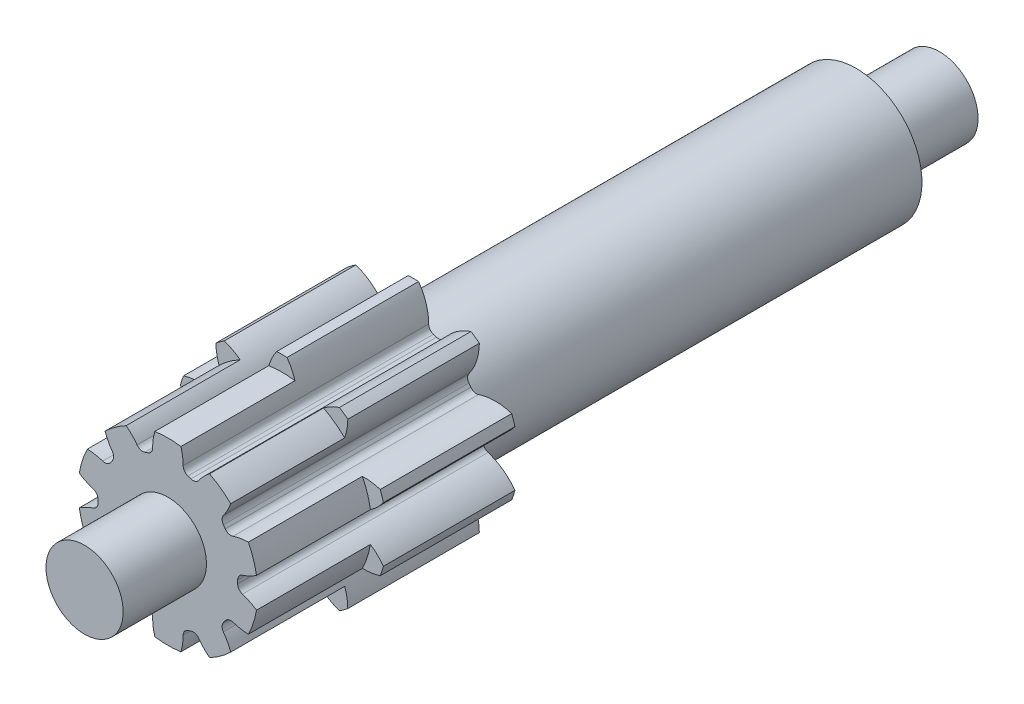
SolidWorks part; units mm, degrees
ref_plane "Front Plane" through (0, 0, 0) normal (0, 0, 1) x (1, 0, 0)
ref_plane "Top Plane" through (0, 0, 0) normal (0, 1, 0) x (1, 0, 0)
ref_plane "Right Plane" through (0, 0, 0) normal (1, 0, 0) x (0, 0, -1)
sketch "Sketch1" plane through (0, 0, 0) normal (0, 0, 1) x (1, 0, 0)
  line L0 (0, 0) -> (0, 1) construction
  line L1 (-0.3214, 1.117) -> (0.3214, 0.883) construction
  circle A0 centre (0, 0) radius 0.8 construction
  circle A1 centre (0, 0) radius 1.2 construction
  circle A2 centre (0, 0) radius 1 construction
  circle A3 centre (0, 0) radius 0.9397 construction
  circle A5 centre (0, 0) radius 0.5 construction
  point P8 (0.1, 0)
  point P13 (5, 0)
  dimension "OD" = 2.4
  dimension "Root Diameter" = 1.6
  dimension "Gear Pitch Diameter" = 2
  dimension "Base Diameter" = 1.8794
  dimension "For Shaft Diameter" = 1
  dimension "Pressure Angle" = 20
  dimension "Number of Teeth" = 10
  dimension "Module" = 0.2
sketch "Sketch2" plane through (0, 0, 0) normal (1, 0, 0) x (0, 0, -1)
  line L0 (-4.875, 0) -> (4.875, 0) construction
  line L1 (4.875, 1.2) -> (4.875, -1.2) construction
  line L3 (-4.875, 1.2) -> (4.875, 1.2) construction
  line L5 (-4.875, 12.5) -> (-4.875, -12.5) construction
  point P2 (0, 1.2)
  dimension "Overall Width" = 9.75
  dimension "Face Width" = 4.875
sketch "Sketch3" plane through (0, 0, 0) normal (0, 0, 1) x (1, 0, 0)
  circle A0 centre (0, 0) radius 1.2
  circle A1 centre (0, 0) radius 1.2 construction
extrude "Boss-Extrude1" add sketch "Sketch3" against normal up to vertex (4.875 mm away) and the other way up to vertex (4.875 mm away) up to point (0, 0, -4.875) other way up to point (0, 0, 4.875)
sketch "Sketch4" plane through (0, 0, 0) normal (0, 0, 1) x (1, 0, 0)
  line L0 (0.7961, -0.0785) -> (0.7961, 0.0785)
  arc A3 (1.1581, 0.3145) -> (1.1581, -0.3145) centre (0, 0) cw
  circle A4 centre (0, 0) radius 1.2 construction
  arc A5 (1.1581, 0.3145) -> (0.7961, 0.0785) centre (0.6623, 0.6793) cw
  circle A6 centre (0, 0) radius 0.8 construction
  arc A7 (1.1581, -0.3145) -> (0.7961, -0.0785) centre (0.6623, -0.6793) ccw
  spline S0 degree 4 poles (0.9302, 0.1332) (0.9306, 0.1332) (0.9319, 0.1334) (0.9341, 0.1339) (0.9378, 0.1349) (0.9425, 0.1363) (0.9484, 0.1382) (0.9553, 0.1409) (0.9629, 0.144) (0.971, 0.1477) (0.979, 0.1517) (0.9868, 0.1559) (0.9946, 0.1603) (1.0039, 0.1659) (1.0149, 0.1729) (1.0275, 0.1817) (1.0414, 0.1921) (1.0554, 0.2034) (1.0688, 0.215) (1.082, 0.2273) (1.0945, 0.2396) (1.1072, 0.2528) (1.1187, 0.2654) (1.1311, 0.28) (1.1411, 0.2921) (1.1562, 0.3118) (1.1625, 0.3205) (1.1719, 0.3338) (1.1749, 0.3384) knots 0 0 0 0 0 0.005377 0.015084 0.028532 0.04661 0.064855 0.092111 0.119476 0.146842 0.174209 0.201575 0.228941 0.256307 0.307035 0.361767 0.4165 0.471232 0.525964 0.580697 0.635429 0.690161 0.744894 0.799626 0.854358 0.909091 1 1 1 1 1 construction
  spline S1 degree 4 poles (0.9302, 0.1332) (0.9306, 0.1332) (0.9319, 0.1334) (0.9341, 0.1339) (0.9378, 0.1349) (0.9425, 0.1363) (0.9484, 0.1382) (0.9553, 0.1409) (0.9629, 0.144) (0.971, 0.1477) (0.979, 0.1517) (0.9868, 0.1559) (0.9946, 0.1603) (1.0039, 0.1659) (1.0149, 0.1729) (1.0275, 0.1817) (1.0414, 0.1921) (1.0554, 0.2034) (1.0688, 0.215) (1.082, 0.2273) (1.0945, 0.2396) (1.1072, 0.2528) (1.1187, 0.2654) (1.1311, 0.28) (1.1411, 0.2921) (1.1508, 0.3048) (1.1556, 0.3112) (1.1581, 0.3145) knots 0 0 0 0 0 0.005377 0.015084 0.028532 0.04661 0.064855 0.092111 0.119476 0.146842 0.174209 0.201575 0.228941 0.256307 0.307035 0.361767 0.4165 0.471232 0.525964 0.580697 0.635429 0.690161 0.744894 0.799626 0.854358 0.909091 0.909091 0.909091 0.909091 0.909091 construction
  spline S2 degree 4 poles (0.9302, -0.1332) (0.9306, -0.1332) (0.9319, -0.1334) (0.9341, -0.1339) (0.9378, -0.1349) (0.9425, -0.1363) (0.9484, -0.1382) (0.9553, -0.1409) (0.9629, -0.144) (0.971, -0.1477) (0.979, -0.1517) (0.9868, -0.1559) (0.9946, -0.1603) (1.0039, -0.1659) (1.0149, -0.1729) (1.0275, -0.1817) (1.0414, -0.1921) (1.0554, -0.2034) (1.0688, -0.215) (1.082, -0.2273) (1.0945, -0.2396) (1.1072, -0.2528) (1.1187, -0.2654) (1.1311, -0.28) (1.1411, -0.2921) (1.1562, -0.3118) (1.1625, -0.3205) (1.1719, -0.3338) (1.1749, -0.3384) knots 0 0 0 0 0 0.005377 0.015084 0.028532 0.04661 0.064855 0.092111 0.119476 0.146842 0.174209 0.201575 0.228941 0.256307 0.307035 0.361767 0.4165 0.471232 0.525964 0.580697 0.635429 0.690161 0.744894 0.799626 0.854358 0.909091 1 1 1 1 1 construction
  spline S3 degree 4 poles (0.9302, -0.1332) (0.9306, -0.1332) (0.9319, -0.1334) (0.9341, -0.1339) (0.9378, -0.1349) (0.9425, -0.1363) (0.9484, -0.1382) (0.9553, -0.1409) (0.9629, -0.144) (0.971, -0.1477) (0.979, -0.1517) (0.9868, -0.1559) (0.9946, -0.1603) (1.0039, -0.1659) (1.0149, -0.1729) (1.0275, -0.1817) (1.0414, -0.1921) (1.0554, -0.2034) (1.0688, -0.215) (1.082, -0.2273) (1.0945, -0.2396) (1.1072, -0.2528) (1.1187, -0.2654) (1.1311, -0.28) (1.1411, -0.2921) (1.1508, -0.3048) (1.1556, -0.3112) (1.1581, -0.3145) knots 0 0 0 0 0 0.005377 0.015084 0.028532 0.04661 0.064855 0.092111 0.119476 0.146842 0.174209 0.201575 0.228941 0.256307 0.307035 0.361767 0.4165 0.471232 0.525964 0.580697 0.635429 0.690161 0.744894 0.799626 0.854358 0.909091 0.909091 0.909091 0.909091 0.909091 construction
  dimension "D1" = 0.1571
extrude "Cut-Extrude1" cut sketch "Sketch4" against normal through all both and the other way through all
fillet "Fillet1" radius 0.0785 2 edges at (0.7961, -0.0785, 0) (0.7961, 0.0785, 0)
pattern_circular "CirPattern1" count 10 over 360 about axis through (0, 0, 0) along (0, 0, 1) of "Cut-Extrude1", "Fillet1"
sketch "Sketch6" plane through (0, 0, 0) normal (0, 1, 0) x (1, 0, 0)
  line L0 (0, 6.2826) -> (0, -4.2534) construction
  line L1 (0, 4.875) -> (0, -4.875) construction
  line L2 (-0.44, 4.875) -> (-1.3, 4.875)
  line L3 (-1.3, 4.875) -> (-1.3, -1.125)
  line L4 (-1.3, -1.125) -> (-0.75, -1.125)
  line L5 (-0.75, -1.125) -> (-0.75, 3.925)
  line L6 (-0.75, 3.925) -> (-0.44, 3.925)
  line L7 (-0.44, 3.925) -> (-0.44, 4.875)
  line L8 (0.0587, 4.875) -> (-0.0587, 4.875) construction
  line L9 (-1.3, -2.625) -> (-1.3, -4.875)
  line L10 (-1.3, -4.875) -> (-0.44, -4.875)
  line L11 (-0.44, -4.875) -> (-0.44, -3.925)
  line L12 (-0.44, -3.925) -> (-1.025, -3.925)
  line L13 (-1.025, -3.925) -> (-1.025, -2.625)
  line L14 (-1.025, -2.625) -> (-1.3, -2.625)
  line L15 (0.0587, -4.875) -> (0.1741, -4.875) construction
  dimension "D1" = 0.88
  dimension "D2" = 1.5
  dimension "D3" = 2.6
  dimension "D4" = 6
  dimension "D5" = 0.95
  dimension "D6" = 2.05
  dimension "D7" = 1.5
  dimension "D8" = 0.95
revolve "Cut-Revolve1" cut sketch "Sketch6" angle 360 about L0
equation "\"Number of Teeth\"= 10"
equation "\"Module\"= 0.2"
equation "\"Diametral Pitch\"= 1 / \"Module\""
equation "\"Dedendum\"= 1.25 / \"Diametral Pitch\""
equation "\"Pitch Diameter\"= \"Module\" * \"Number of Teeth\""
equation "\"Root Diameter\"= \"Pitch Diameter\" - ( 2 * \"Dedendum\" ) + 0.1"
equation "\"Root Diameter@Sketch1\"=\"Root Diameter\""
equation "\"OD@Sketch1\" = \"Outside Diameter\""
equation "\"D1@CirPattern1\"=\"Number of Teeth\""
equation "\"Pressure Angle\"= 20"
equation "\"Base Diameter\"= \"Pitch Diameter\" * cos ( \"Pressure Angle\" )"
equation "\"Outside Diameter\"= ( \"Number of Teeth\" + 2 ) / \"Diametral Pitch\""
equation "\"Pitch Angle\"= 360deg / \"Number of Teeth\""
equation "\"Alpha\"= sqr ( \"Pitch Diameter\" ^ 2 - \"Base Diameter\" ^ 2 ) / \"Base Diameter\" * 180 / PI - \"Pressure Angle\""
equation "\"Beta\"= ( \"Pitch Angle\" / 4 - \"Alpha\" )"
equation "\"Phi\"= sqr ( ( \"Outside Diameter\" / 2 ) ^ 2 - ( \"Base Diameter\" / 2 ) ^ 2 ) / ( \"Base Diameter\" / 2 )"
equation "\"Addendum\"= 1 / \"Diametral Pitch\""
equation "\"WorkingDepth\"= 2 / \"Diametral Pitch\""
equation "\"WholeDepth\"= 2.25 / \"Diametral Pitch\""
equation "\"Clearance\"= 0.25 / \"Diametral Pitch\""
equation "\"ToothThickness\"= ( pi * 2 ) / \"Diametral Pitch\""
equation "\"CircularPitch\"= pi / \"Diametral Pitch\""
equation "\"Number of Teeth@Sketch1\"=\"Number of Teeth\""
equation "\"Module@Sketch1\"=\"Module\""
equation "\"Pressure Angle@Sketch1\"=\"Pressure Angle\""
equation "\"Gear Pitch Diameter@Sketch1\"=\"Pitch Diameter\""
equation "\"Base Diameter@Sketch1\"=\"Base Diameter\""
equation "\"Fillet\"= \"Clearance\" * cos ( \"Pressure Angle\" ) * tan ( ( 90 + \"Pressure Angle\" ) / 2 )"
equation "\"D1\"= \"Fillet\""
equation "\"D1\"= \"Set Screw Pitch@Sketch1\" * .75"
equation "\"D1\"= \"Set Screw Diameter@Sketch1\" / 2"
equation "\"D3\"= \"Set Screw Pitch@Sketch1\" +  ( \"Hub Diameter@Sketch1\" / 2 ) "
equation "\"D4\"= \"Set Screw Pitch@Sketch1\""
equation "\"D2\"= \"Fillet\" * 2"
equation "\"D1\"= \"Fillet\" * 2"
equation "\"D1@Sketch4\"=\"CircularPitch\"*0.25"
equation "\"D1@Fillet1\"=\"CircularPitch\"*0.125"
